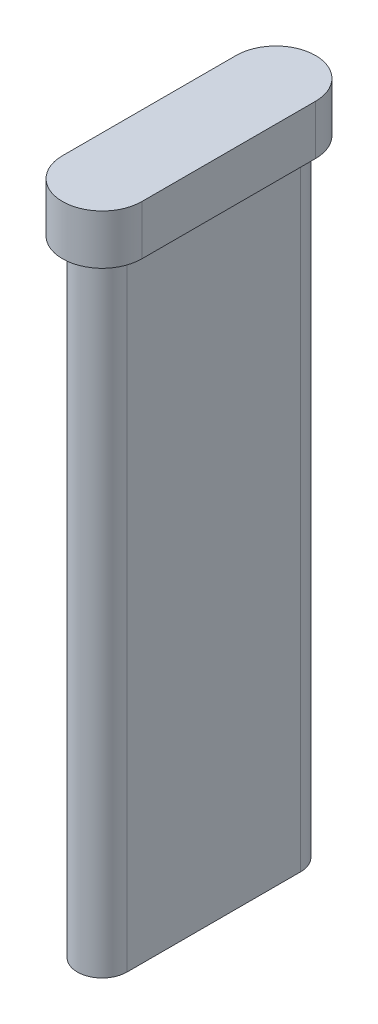
SolidWorks part; units mm, degrees
material "K110"
ref_plane "Front Plane" through (0, 0, 0) normal (0, 0, 1) x (1, 0, 0)
ref_plane "Top Plane" through (0, 0, 0) normal (0, 1, 0) x (1, 0, 0)
ref_plane "Right Plane" through (0, 0, 0) normal (1, 0, 0) x (0, 0, -1)
sketch "Sketch1" plane through (0, 0, 0) normal (0, 1, 0) x (1, 0, 0)
  line L0 (0, -8.75) -> (0, 8.75) construction
  line L1 (-2.5, -8.75) -> (-2.5, 8.75)
  line L2 (2.5, -8.75) -> (2.5, 8.75)
  arc A0 (-2.5, -8.75) -> (2.5, -8.75) centre (0, -8.75) ccw
  arc A1 (2.5, 8.75) -> (-2.5, 8.75) centre (0, 8.75) ccw
  point P2 (0, 0)
  dimension "D2" = 2.5
  dimension "D1" = 17.5
extrude "Boss-Extrude1" add sketch "Sketch1" against normal blind 68
sketch "Sketch2" plane through (0, 0, 0) normal (0, 1, 0) x (1, 0, 0)
  line L4 (4, -8.75) -> (4, 8.75)
  line L5 (-4, 8.75) -> (-4, -8.75)
  line L6 (4, -8.75) -> (4, 8.75)
  line L7 (-4, 8.75) -> (-4, -8.75)
  arc A4 (4, 8.75) -> (-4, 8.75) centre (0, 8.75) ccw
  arc A5 (-4, -8.75) -> (4, -8.75) centre (0, -8.75) ccw
  arc A6 (4, 8.75) -> (-4, 8.75) centre (0, 8.75) ccw
  arc A7 (-4, -8.75) -> (4, -8.75) centre (0, -8.75) ccw
  dimension "D1" = 1.5
extrude "Boss-Extrude2" add sketch "Sketch2" against normal blind 5
